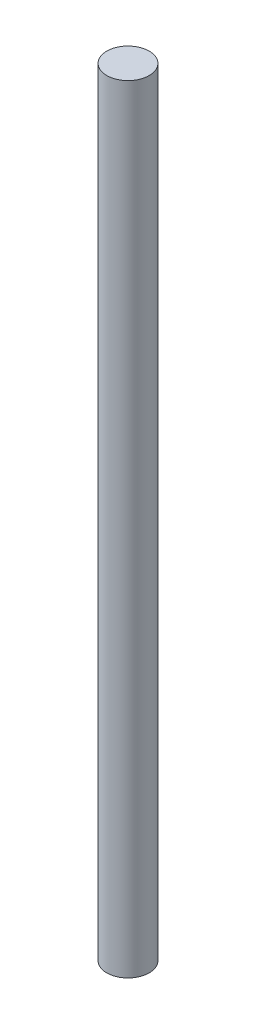
SolidWorks part; units mm, degrees
ref_plane "Alzado" through (0, 0, 0) normal (0, 0, 1) x (1, 0, 0)
ref_plane "Planta" through (0, 0, 0) normal (0, 1, 0) x (1, 0, 0)
ref_plane "Vista lateral" through (0, 0, 0) normal (1, 0, 0) x (0, 0, -1)
sketch "Croquis1" plane through (0, 0, 0) normal (0, 1, 0) x (1, 0, 0)
  circle A0 centre (0, 0) radius 3
  dimension "D1" = 6
extrude "Saliente-Extruir1" add sketch "Croquis1" along normal mid plane 110
